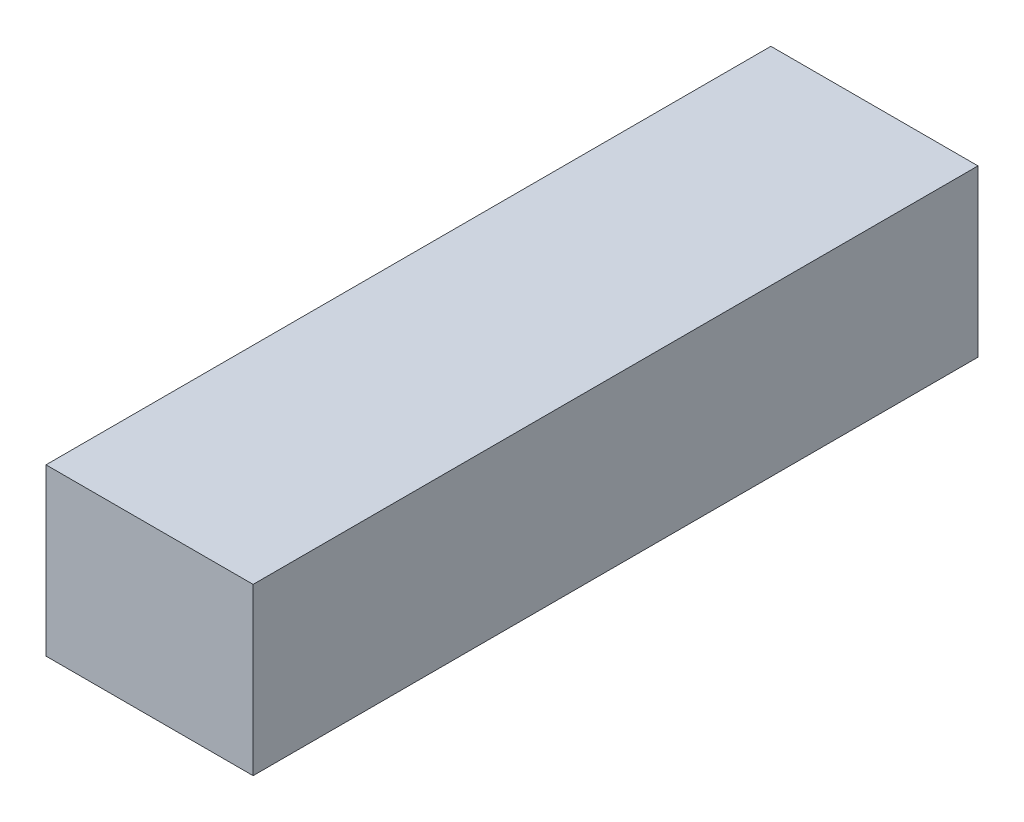
SolidWorks part; units mm, degrees
ref_plane "Front Plane" through (0, 0, 0) normal (0, 0, 1) x (1, 0, 0)
ref_plane "Top Plane" through (0, 0, 0) normal (0, 1, 0) x (1, 0, 0)
ref_plane "Right Plane" through (0, 0, 0) normal (1, 0, 0) x (0, 0, -1)
sketch "Sketch1" plane through (0, 0, 0) normal (0, 1, 0) x (1, 0, 0)
  line L1 (-12.7, -44.45) -> (12.7, -44.45)
  line L2 (-12.7, -44.45) -> (-12.7, 44.45)
  line L3 (-12.7, 44.45) -> (12.7, 44.45)
  line L4 (12.7, -44.45) -> (12.7, 44.45)
  line L5 (-12.7, -44.45) -> (12.7, 44.45) construction
  line L6 (-12.7, 44.45) -> (12.7, -44.45) construction
  point P0 (0, 0)
  dimension "D1" = 25.4
  dimension "D2" = 88.9
extrude "Boss-Extrude1" add sketch "Sketch1" along normal blind 20.32 contours L2 L3 L4 L1
sketch "Sketch2" plane through (0, 0, 44.45) normal (0, 0, 1) x (1, 0, 0)
  line L0 (-22.225, 10.16) -> (22.225, 10.16) construction
  line L2 (0, 20.32) -> (0, 0) construction
  line L3 (-22.225, 10.16) -> (22.225, 10.16) construction
  line L4 (-22.225, 13.462) -> (22.225, 13.462)
  line L5 (-22.225, 6.858) -> (22.225, 6.858)
  line L6 (-12.7, 20.32) -> (12.7, 20.32) construction
  circle A0 centre (-22.225, 10.16) radius 2.032
  circle A1 centre (22.225, 10.16) radius 2.032
  arc A2 (-22.225, 13.462) -> (-22.225, 6.858) centre (-22.225, 10.16) ccw
  arc A3 (22.225, 6.858) -> (22.225, 13.462) centre (22.225, 10.16) ccw
  point P5 (0, 10.16)
  dimension "D2" = 4.064
  dimension "D4" = 1.27
  dimension "D1" = 44.45
sketch "Sketch3" plane through (-12.7, 0, 0) normal (-1, 0, 0) x (0, 0, 1)
  line L0 (-44.45, 10.16) -> (-6.35, 10.16) construction
  line L1 (-44.45, 20.32) -> (-44.45, 0) construction
  line L3 (-31.1785, 13.3985) -> (-24.7015, 13.3985)
  line L4 (-31.1785, 13.3985) -> (-31.1785, 6.9215)
  line L5 (-31.1785, 6.9215) -> (-24.7015, 6.9215)
  line L6 (-24.7015, 13.3985) -> (-24.7015, 6.9215)
  line L7 (-31.1785, 13.3985) -> (-24.7015, 6.9215) construction
  line L8 (-31.1785, 6.9215) -> (-24.7015, 13.3985) construction
  circle A0 centre (-27.94, 10.16) radius 13.97
  circle A1 centre (-7.62, 10.16) radius 7.62
  circle A2 centre (-27.94, 10.16) radius 11.049
  circle A3 centre (-27.94, 10.16) radius 12.065
  circle A5 centre (-27.94, 10.16) radius 4.5799
  circle A6 centre (-7.62, 10.16) radius 2.032
  dimension "D1" = 27.94
  dimension "D2" = 15.24
  dimension "D5" = 22.098
  dimension "D6" = 24.13
  dimension "D8" = 4.064
  dimension "D3" = 16.51
  dimension "D4" = 38.1
  dimension "D7" = 6.477
  dimension "D9" = 20.32
